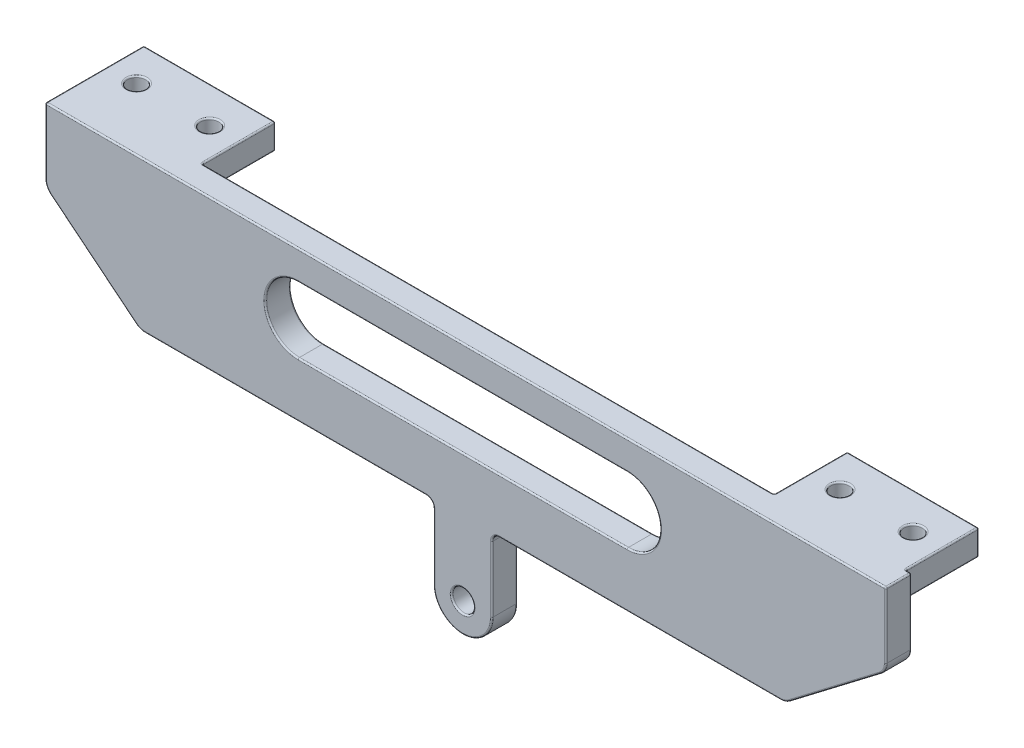
SolidWorks part; units mm, degrees
ref_plane "Front Plane" through (0, 0, 0) normal (0, 0, 1) x (1, 0, 0)
ref_plane "Top Plane" through (0, 0, 0) normal (0, 1, 0) x (1, 0, 0)
ref_plane "Right Plane" through (0, 0, 0) normal (1, 0, 0) x (0, 0, -1)
sketch "Sketch2" plane through (0, 0, 0) normal (0, 0, 1) x (1, 0, 0)
  line L0 (-100, 0) -> (100, 0) construction
  line L1 (-100, 0) -> (0, 100) construction
  line L2 (0, 100) -> (100, 0) construction
  line L3 (0, 0) -> (-52.6991, 47.3009) construction
  line L4 (-40, 60) -> (40, 60) construction
  line L5 (0, 100) -> (0, 60) construction
  circle A0 centre (-100, 0) radius 20
  circle A1 centre (0, 0) radius 20
  circle A2 centre (100, 0) radius 20
  point P2 (0, 0)
  dimension "D5" = 40
  dimension "D1" = 200
  dimension "D2" = 93.09
  dimension "D3" = 80
  dimension "D4" = 90
sketch "Sketch3" plane through (0, 0, 0) normal (0, 0, 1) x (1, 0, 0)
  line L0 (-40, 60) -> (-56.5165, 43.4835) construction
  line L1 (75.9584, 9.8995) -> (90.1005, 24.0416) construction
  line L2 (-40, 60) -> (40, 60) construction
  line L3 (40, 60) -> (86.565, 13.435) construction
  line L4 (0, 100) -> (100, 0) construction
  line L5 (86.565, 13.435) -> (40, 60) construction
  line L6 (-100, 0) -> (0, 100) construction
  line L7 (44.1421, 70) -> (93.636, 20.5061)
  line L8 (-44.1421, 70) -> (44.1421, 70)
  line L9 (-44.1421, 70) -> (-63.5876, 50.5546)
  line L10 (35.8579, 50) -> (79.4939, 6.364)
  line L11 (-35.8579, 50) -> (35.8579, 50)
  line L12 (-35.8579, 50) -> (-49.4454, 36.4124)
  line L13 (-63.5876, 50.5546) -> (-49.4454, 36.4124)
  line L14 (79.4939, 6.364) -> (93.636, 20.5061)
  line L15 (81.9688, 8.8388) -> (95.4038, -4.5962)
  line L16 (90.9809, 17.8509) -> (104.534, 4.6576)
  line L17 (-3.4304, 82.6944) -> (-6, 70)
  line L18 (0, 100) -> (0, 60) construction
  line L19 (3.4304, 82.6944) -> (6, 70)
  circle A0 centre (100, 0) radius 3.5
  circle A1 centre (100, 0) radius 10 construction
  arc A2 (95.4038, -4.5962) -> (104.534, 4.6576) centre (100, 0) ccw
  circle A3 centre (100, 0) radius 0.5
  circle A4 centre (100, 0) radius 20 construction
  circle A5 centre (100, 0) radius 6.5 construction
  circle A6 centre (79.4939, 13.435) radius 1
  circle A7 centre (86.565, 20.5061) radius 1
  circle A8 centre (0, 60) radius 1.5
  circle A11 centre (0, 82) radius 1.5
  arc A12 (3.4304, 82.6944) -> (-3.4304, 82.6944) centre (0, 82) ccw
  circle A13 centre (0, 82) radius 3.5 construction
  circle A14 centre (-52.6991, 47.3009) radius 1
  dimension "D4" = 20
  dimension "D5" = 7
  dimension "D10" = 2
  dimension "D11" = 3
  dimension "D15" = 2
  dimension "D3" = 27.5
  dimension "D8" = 19
  dimension "D9" = 5
  dimension "D12" = 2
  dimension "D14" = 6
  dimension "D13" = 6
  dimension "D16" = 5
  dimension "D17" = 5
  dimension "D18" = 12
  dimension "D1" = 10
  dimension "D2" = 10
  dimension "D6" = 3
  dimension "D7" = 3
sketch "Sketch4" plane through (0, 0, 0) normal (0, 0, 1) x (1, 0, 0)
  line L0 (-100, 0) -> (100, 0) construction
  line L1 (-88.5703, 11.4297) -> (-52.6991, 47.3009) construction
  line L2 (-100, 0) -> (0, 100) construction
  line L3 (-52.6991, 47.3009) -> (-14.1397, 12.6913) construction
  line L4 (0, 0) -> (-52.6991, 47.3009) construction
  line L5 (-79.4939, 6.364) -> (-52.3277, 33.5302)
  line L6 (-52.3277, 33.5302) -> (-20.8193, 5.2493)
  line L7 (-93.636, 20.5061) -> (-53.0706, 61.0716)
  line L8 (-53.0706, 61.0716) -> (-7.4601, 20.1332)
  line L9 (-95.6414, 18.5007) -> (-53.0706, 61.0716) construction
  line L10 (-81.4993, 4.3586) -> (-52.3277, 33.5302) construction
  line L11 (-7.4601, 20.1332) -> (-20.8193, 5.2493)
  line L13 (-79.4939, 6.364) -> (-93.636, 20.5061)
  line L14 (-91.1612, 18.0312) -> (-104.5962, 4.5962)
  line L15 (-81.9688, 8.8388) -> (-95.4038, -4.5962)
  line L16 (-9.9683, 17.3388) -> (4.2763, 4.8952)
  line L17 (-18.4815, 7.854) -> (-4.3418, -4.8373)
  line L18 (9.9995, -0.1043) -> (10.0659, -0.1623)
  line L19 (-85.2086, 28.9335) -> (-71.0665, 14.7914) construction
  line L20 (-25.2845, 9.2571) -> (-11.9252, 24.141) construction
  circle A0 centre (-100, 0) radius 10 construction
  circle A1 centre (0, 0) radius 10 construction
  circle A6 centre (-100, 0) radius 3.5
  circle A7 centre (0, 0) radius 3.5
  arc A8 (-104.5962, 4.5962) -> (-95.4038, -4.5962) centre (-100, 0) ccw
  arc A9 (-4.3418, -4.8373) -> (4.2763, 4.8952) centre (0, 0) ccw
  circle A10 centre (0, 0) radius 20 construction
  circle A11 centre (0, 0) radius 6.5 construction
  circle A12 centre (-100, 0) radius 6.5 construction
  circle A13 centre (-81.6731, 25.398) radius 1
  circle A14 centre (-74.602, 18.3269) radius 1
  circle A15 centre (-21.9447, 12.9781) radius 1
  circle A16 centre (-15.2651, 20.42) radius 1
  dimension "D1" = 20
  dimension "D2" = 7
  dimension "D10" = 5
  dimension "D13" = 2
  dimension "D7" = 19
  dimension "D8" = 19
  dimension "D9" = 5
  dimension "D11" = 5
  dimension "D12" = 5
  dimension "D14" = 6
  dimension "D3" = 3
  dimension "D4" = 3
  dimension "D5" = 10
  dimension "D6" = 10
sketch "Sketch5" plane through (0, 0, 0) normal (0, 0, 1) x (1, 0, 0)
  line L13 (-44.1421, 70) -> (44.1421, 70)
  line L14 (44.1421, 70) -> (57.8914, 80.5)
  line L16 (57.8914, 80.5) -> (57.8914, 90.5)
  line L17 (57.8914, 90.5) -> (-57.1086, 90.5)
  line L18 (-57.1086, 90.5) -> (-57.1086, 80.5)
  line L19 (-57.1086, 80.5) -> (-44.1421, 70)
  line L20 (-4, 60) -> (-4, 70)
  line L21 (4, 60) -> (4, 70)
  line L22 (-22.5, 82) -> (22.5, 82) construction
  line L23 (0, 100) -> (0, 60) construction
  line L24 (-22.5, 86.5) -> (22.5, 86.5)
  line L25 (-22.5, 77.5) -> (22.5, 77.5)
  circle A0 centre (0, 60) radius 1.5 construction
  circle A1 centre (0, 60) radius 1.5
  arc A2 (-4, 60) -> (4, 60) centre (0, 60) ccw
  circle A3 centre (0, 60) radius 4 construction
  arc A4 (-22.5, 86.5) -> (-22.5, 77.5) centre (-22.5, 82) ccw
  arc A5 (22.5, 77.5) -> (22.5, 86.5) centre (22.5, 82) ccw
  point P21 (0, 82)
  dimension "D1" = 115
  dimension "D2" = 10
  dimension "D3" = 2.5
  dimension "D4" = 45
  dimension "D5" = 9
  dimension "D6" = 4
  dimension "D7" = 141
sketch "Sketch6" plane through (0, 0, 0) normal (0, 0, 1) x (1, 0, 0)
  line L0 (-4, 60) -> (-4, 70) construction
  line L1 (4, 60) -> (4, 70) construction
  line L2 (22.5, 86.5) -> (-22.5, 86.5)
  line L3 (-22.5, 77.5) -> (22.5, 77.5)
  line L4 (22.5, 86.5) -> (-22.5, 86.5)
  line L5 (-22.5, 77.5) -> (22.5, 77.5)
  line L6 (-44.1421, 70) -> (44.1421, 70)
  line L7 (44.1421, 70) -> (57.8914, 80.5)
  line L8 (57.8914, 80.5) -> (57.8914, 90.5)
  line L9 (57.8914, 90.5) -> (-57.1086, 90.5)
  line L10 (-57.1086, 90.5) -> (-57.1086, 80.5)
  line L11 (-57.1086, 80.5) -> (-44.1421, 70)
  line L12 (-44.1421, 70) -> (-4, 70)
  line L13 (44.1421, 70) -> (57.8914, 80.5)
  line L14 (57.8914, 80.5) -> (57.8914, 90.5)
  line L15 (57.8914, 90.5) -> (-57.1086, 90.5)
  line L16 (-57.1086, 90.5) -> (-57.1086, 80.5)
  line L17 (-57.1086, 80.5) -> (-44.1421, 70)
  line L18 (-4, 60) -> (-4, 70)
  line L19 (4, 60) -> (4, 70)
  line L20 (4, 70) -> (44.1421, 70)
  arc A0 (-4, 60) -> (4, 60) centre (0, 60) ccw construction
  circle A1 centre (0, 60) radius 1.5
  circle A2 centre (0, 60) radius 1.5
  arc A3 (-4, 60) -> (4, 60) centre (0, 60) ccw
  arc A4 (22.5, 77.5) -> (22.5, 86.5) centre (22.5, 82) ccw
  arc A5 (-22.5, 86.5) -> (-22.5, 77.5) centre (-22.5, 82) ccw
  arc A6 (22.5, 77.5) -> (22.5, 86.5) centre (22.5, 82) ccw
  arc A7 (-22.5, 86.5) -> (-22.5, 77.5) centre (-22.5, 82) ccw
  dimension "D1" = 0
  dimension "D2" = 0
  dimension "D3" = 0
extrude "Boss-Extrude1" add sketch "Sketch6" along normal blind 3.5
sketch "Sketch8" plane through (0, 90.5, 0) normal (0, 1, 0) x (1, 0, 0)
  line L0 (0, 0) -> (0, 22.284) construction
  line L1 (-57.1086, 5) -> (-39.1086, 5) construction
  line L2 (-57.1086, 0) -> (-39.1086, 0)
  line L3 (-57.1086, 0) -> (-57.1086, 10)
  line L4 (-57.1086, 10) -> (-39.1086, 10)
  line L5 (-39.1086, 0) -> (-39.1086, 10)
  line L6 (-39.1086, 5) -> (-48.1086, 5) construction
  line L7 (-48.1086, 5) -> (-48.1086, 10) construction
  line L8 (48.1086, 5) -> (48.1086, 10) construction
  line L9 (39.1086, 5) -> (48.1086, 5) construction
  line L10 (57.1086, 5) -> (39.1086, 5) construction
  line L11 (39.1086, 0) -> (39.1086, 10)
  line L12 (57.1086, 10) -> (39.1086, 10)
  line L13 (57.1086, 0) -> (57.1086, 10)
  line L14 (57.1086, 0) -> (39.1086, 0)
  circle A0 centre (-53.1086, 5) radius 1.25
  circle A1 centre (-43.1086, 5) radius 1.25
  circle A2 centre (43.1086, 5) radius 1.25
  circle A3 centre (53.1086, 5) radius 1.25
  dimension "D4" = 2.5
  dimension "D1" = 18
  dimension "D2" = 10
  dimension "D3" = 10
extrude "Boss-Extrude2" add sketch "Sketch8" against normal blind 3.5
fillet "Fillet1" radius 2 4 edges at (57.8914, 80.5, 1.75) (44.1421, 70, 1.75) (-44.1421, 70, 1.75) (-57.1086, 80.5, 1.75)
fillet "Fillet2" radius 1 2 edges at (-4, 70, 1.75) (4, 70, 1.75)
fillet "Fillet3" radius 0.2 73 edges at (54.3586, 90.5, -5) (54.3586, 87, -5) (44.3586, 90.5, -5) (44.3586, 87, -5) (57.1086, 90.5, -5) (57.1086, 87, -5) (48.1086, 90.5, -10) (48.1086, 87, -10) (39.1086, 90.5, -5) (39.1086, 87, -5) (48.1086, 87, 0) (57.1086, 88.75, 0) (57.1086, 88.75, -10) (39.1086, 88.75, -10) (39.1086, 88.75, 0) (-44.3586, 90.5, -5) (-44.3586, 87, -5) (-54.3586, 90.5, -5) (-54.3586, 87, -5) (-39.1086, 90.5, -5) (-39.1086, 87, -5) (-48.1086, 90.5, -10) (-48.1086, 87, -10) (-57.1086, 87, -5) (-48.1086, 87, 0) (-39.1086, 88.75, 0) (-39.1086, 88.75, -10) (-57.1086, 88.75, -10) (0, 77.5, 0) (27, 82, 0) (0, 86.5, 0) (-27, 82, 3.5) (0, 77.5, 3.5) (27, 82, 3.5) (0, 86.5, 3.5) (1.5, 60, 0) (1.5, 60, 3.5) (-50.5299, 75.1727, 0) (-24.2169, 70, 0) (-4, 64.5, 0) (0, 56, 0) (4, 64.5, 0) (24.2329, 70, 0) (50.8925, 75.1551, 0) (57.8914, 85.9946, 0) (0, 90.5, 0) (57.5, 90.5, 0) (-57.1086, 84.227, 0) (-50.5299, 75.1727, 3.5) (-24.2169, 70, 3.5) (-4, 64.5, 3.5) (0, 56, 3.5) (4, 64.5, 3.5) (24.2329, 70, 3.5) (50.8925, 75.1551, 3.5) (57.8914, 85.9946, 3.5) (0.3914, 90.5, 3.5) (-57.1086, 85.977, 3.5) (-57.1086, 90.5, -3.25) (57.8914, 90.5, 1.75) (-56.9137, 80.5929, 0) (-44.1015, 70.1147, 0) (44.1065, 70.1054, 0) (57.6842, 80.6025, 0) (-56.9137, 80.5929, 3.5) (-44.1015, 70.1147, 3.5) (44.1065, 70.1054, 3.5) (57.6842, 80.6025, 3.5) (-4.2929, 69.7071, 0) (-4.2929, 69.7071, 3.5) (4.2929, 69.7071, 0) (4.2929, 69.7071, 3.5) (-27, 82, 0)
